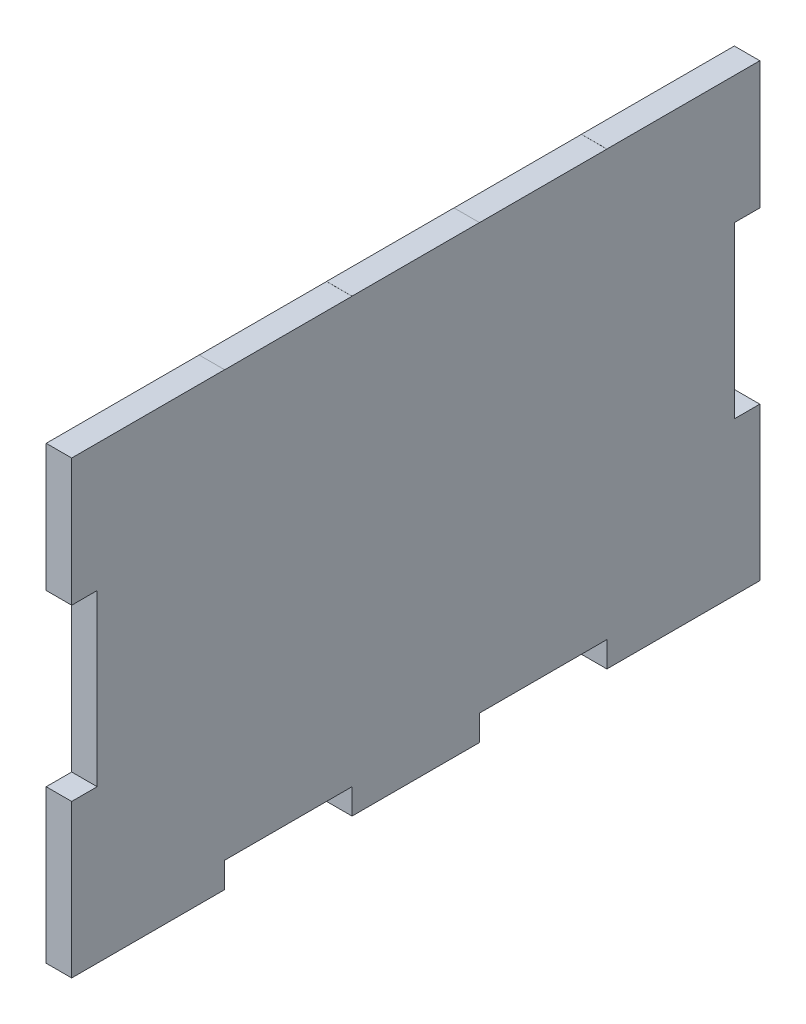
SolidWorks part; units mm, degrees
ref_plane "Plano frontal" through (0, 0, 0) normal (0, 0, 1) x (1, 0, 0)
ref_plane "Plano superior" through (0, 0, 0) normal (0, 1, 0) x (1, 0, 0)
ref_plane "Plano direito" through (0, 0, 0) normal (1, 0, 0) x (0, 0, -1)
sketch "Esboço1" plane through (0, 0, 0) normal (1, 0, 0) x (0, 0, -1)
  line L1 (75, -50) -> (-75, -50)
  line L2 (75, -50) -> (75, 50)
  line L3 (75, 50) -> (-75, 50)
  line L4 (-75, -50) -> (-75, 50)
  line L5 (75, -50) -> (-75, 50) construction
  line L6 (75, 50) -> (-75, -50) construction
  point P0 (0, 0)
  dimension "D1" = 100
  dimension "D2" = 150
extrude "Ressalto-extrusão1" add sketch "Esboço1" along normal blind 6
sketch "Esboço3" plane through (0, 50, 0) normal (0, 1, 0) x (1, 0, 0)
  line L0 (0, 75) -> (0, -75) construction
  line L1 (6, 75) -> (0, 75)
  line L2 (6, 75) -> (6, 45)
  line L3 (6, 45) -> (0, 45)
  line L4 (0, 75) -> (0, 45)
  line L5 (6, 75) -> (6, -75) construction
  line L6 (0, 15) -> (6, 15)
  line L7 (0, 15) -> (0, -15)
  line L8 (0, -15) -> (6, -15)
  line L9 (6, 15) -> (6, -15)
  line L11 (0, -75) -> (6, -75)
  line L12 (0, -75) -> (0, -45)
  line L13 (0, -45) -> (6, -45)
  line L14 (6, -75) -> (6, -45)
  dimension "D1" = 30
  dimension "D2" = 30
  dimension "D3" = 30
  dimension "D4" = 30
  dimension "D5" = 30
extrude "Ressalto-extrusão2" add sketch "Esboço3" along normal blind 6
sketch "Esboço4" plane through (0, -50, 0) normal (0, -1, 0) x (1, 0, 0)
  line L0 (0, 75) -> (0, -75) construction
  line L1 (6, 75) -> (0, 75)
  line L2 (6, 75) -> (6, 45)
  line L3 (6, 45) -> (0, 45)
  line L4 (0, 75) -> (0, 45)
  line L5 (6, 75) -> (6, -75) construction
  line L6 (0, 15) -> (6, 15)
  line L7 (0, 15) -> (0, -15)
  line L8 (0, -15) -> (6, -15)
  line L9 (6, 15) -> (6, -15)
  line L11 (0, -75) -> (6, -75)
  line L12 (0, -75) -> (0, -45)
  line L13 (0, -45) -> (6, -45)
  line L14 (6, -75) -> (6, -45)
  line L15 (6, -45) -> (6, -75) construction
  dimension "D1" = 30
  dimension "D2" = 30
  dimension "D3" = 30
  dimension "D4" = 30
extrude "Ressalto-extrusão3" add sketch "Esboço4" along normal blind 6
sketch "Esboço6" plane through (0, 0, 75) normal (0, 0, 1) x (1, 0, 0)
  line L0 (6, 56) -> (6, -56) construction
  line L1 (0, 56) -> (6, 56)
  line L2 (0, 56) -> (0, 20)
  line L3 (0, 20) -> (6, 20)
  line L4 (6, 56) -> (6, 20)
  line L6 (0, -56) -> (6, -56)
  line L7 (0, -56) -> (0, -20)
  line L8 (0, -20) -> (6, -20)
  line L9 (6, -56) -> (6, -20)
  dimension "D1" = 36
  dimension "D2" = 36
extrude "Ressalto-extrusão4" add sketch "Esboço6" along normal blind 6
sketch "Esboço7" plane through (0, 0, -75) normal (0, 0, -1) x (-1, 0, 0)
  line L0 (0, -56) -> (0, 56) construction
  line L1 (-6, -56) -> (0, -56)
  line L2 (-6, -56) -> (-6, -20)
  line L3 (-6, -20) -> (0, -20)
  line L4 (0, -56) -> (0, -20)
  line L5 (-6, -56) -> (-6, 56) construction
  line L6 (0, 56) -> (-6, 56)
  line L7 (0, 56) -> (0, 20)
  line L8 (0, 20) -> (-6, 20)
  line L9 (-6, 56) -> (-6, 20)
  dimension "D1" = 36
  dimension "D2" = 36
  dimension "D3" = 40
extrude "Ressalto-extrusão5" add sketch "Esboço7" along normal blind 6
sketch "Esboço8" plane through (0, 0, 0) normal (-1, 0, 0) x (0, 0, 1)
  line L0 (81, 56) -> (81, 20) construction
  line L1 (-81, 56) -> (81, 56)
  line L2 (-81, 56) -> (-81, 50.0175)
  line L3 (-81, 50.0175) -> (81, 50.0175)
  line L4 (81, 56) -> (81, 50.0175)
extrude "Corte-extrusão1" cut sketch "Esboço8" against normal blind 6
